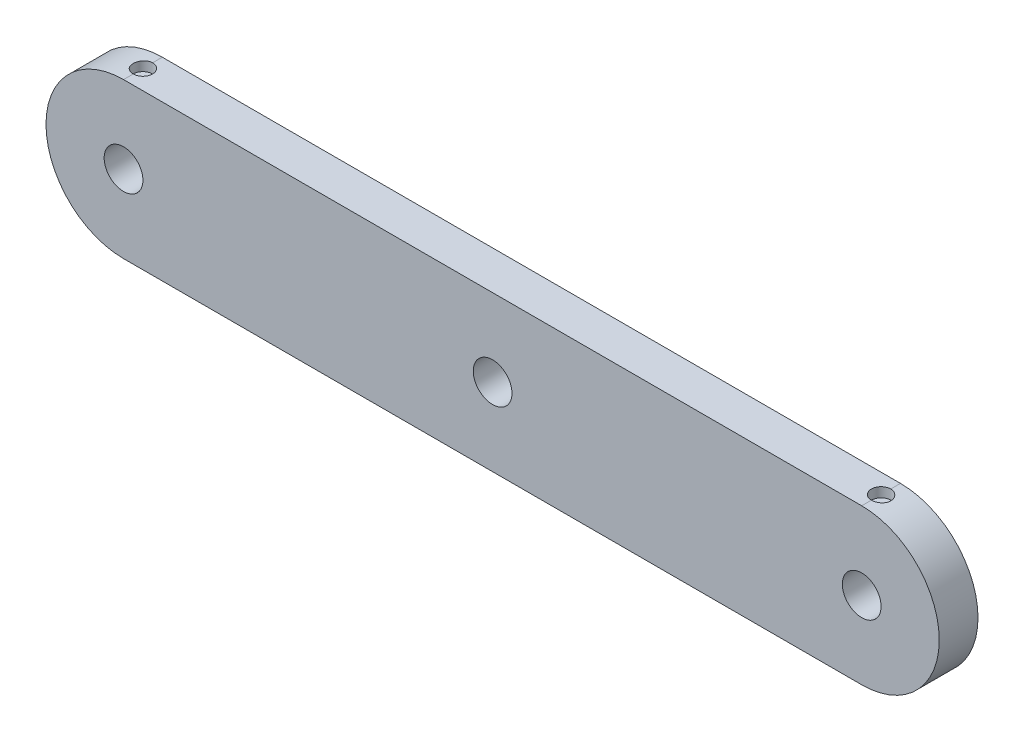
SolidWorks part; units mm, degrees
ref_plane "Front Plane" through (0, 0, 0) normal (0, 0, 1) x (1, 0, 0)
ref_plane "Top Plane" through (0, 0, 0) normal (0, 1, 0) x (1, 0, 0)
ref_plane "Right Plane" through (0, 0, 0) normal (1, 0, 0) x (0, 0, -1)
sketch "Sketch1" plane through (0, 0, 0) normal (0, 0, 1) x (1, 0, 0)
  line L2 (-19.042, 4) -> (19.042, 4)
  line L3 (-19.042, -4) -> (19.042, -4)
  circle A5 centre (0, 0) radius 1
  circle A6 centre (19.042, 0) radius 1
  circle A7 centre (-19.042, 0) radius 1
  arc A8 (19.042, -4) -> (19.042, 4) centre (19.042, 0) ccw
  arc A9 (-19.042, 4) -> (-19.042, -4) centre (-19.042, 0) ccw
  dimension "D1" = 2
  dimension "D2" = 2
  dimension "D3" = 2
  dimension "D4" = 38.084
  dimension "D6" = 4
  dimension "D5" = 4
extrude "Boss-Extrude1" add sketch "Sketch1" along normal blind 2
sketch "Sketch2" plane through (0, 4, 0) normal (0, 1, 0) x (1, 0, 0)
  line L0 (-19.042, -2) -> (-19.042, 0) construction
  circle A0 centre (-19.042, -1) radius 0.5
  circle A1 centre (19.042, -1) radius 0.5
extrude "Cut-Extrude1" cut sketch "Sketch2" against normal blind 0.5
sketch "Sketch3" plane through (0, -4, 0) normal (0, -1, 0) x (1, 0, 0)
  circle A0 centre (0, 1) radius 0.5
extrude "Cut-Extrude2" cut sketch "Sketch3" against normal blind 0.5
